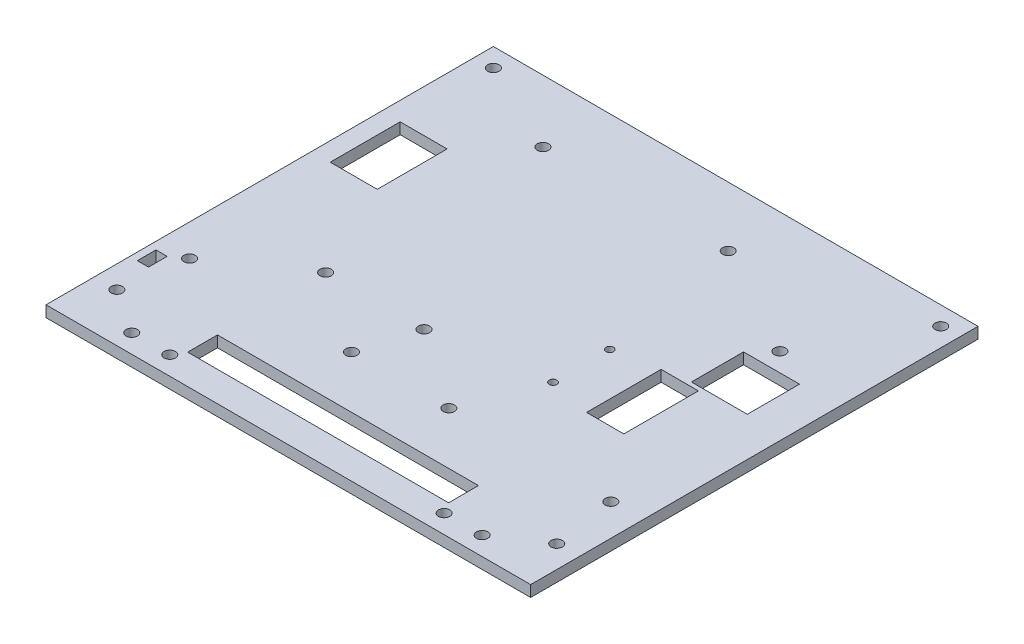
SolidWorks part; units mm, degrees
ref_plane "Front Plane" through (0, 0, 0) normal (0, 0, 1) x (1, 0, 0)
ref_plane "Top Plane" through (0, 0, 0) normal (0, 1, 0) x (1, 0, 0)
ref_plane "Right Plane" through (0, 0, 0) normal (1, 0, 0) x (0, 0, -1)
sketch "Sketch1" plane through (0, 0, 0) normal (0, 1, 0) x (1, 0, 0)
  line L0 (65, 0) -> (65, -120) construction
  line L1 (0, 0) -> (130, 0)
  line L2 (0, 0) -> (0, -92.5)
  line L3 (0, -120) -> (130, -120)
  line L4 (130, 0) -> (130, -92.5)
  line L5 (30, -104) -> (100, -104)
  line L6 (30, -104) -> (30, -112)
  line L7 (30, -112) -> (100, -112)
  line L8 (100, -104) -> (100, -112)
  line L9 (2, -92.5) -> (5, -92.5)
  line L10 (97.5, -52.5) -> (107.5, -52.5)
  line L11 (97.5, -52.5) -> (97.5, -72.5)
  line L12 (97.5, -72.5) -> (107.5, -72.5)
  line L13 (107.5, -52.5) -> (107.5, -72.5)
  line L14 (104.5, -51.38) -> (119.5, -51.38)
  line L15 (104.5, -51.38) -> (104.5, -37.38)
  line L16 (104.5, -37.38) -> (119.5, -37.38)
  line L17 (119.5, -51.38) -> (119.5, -37.38)
  line L18 (104.5, -51.38) -> (119.5, -37.38) construction
  line L19 (104.5, -37.38) -> (119.5, -51.38) construction
  line L20 (5, -92.5) -> (5, -97.5)
  line L21 (5, -97.5) -> (2, -97.5)
  line L25 (0, -97.5) -> (0, -120)
  line L26 (130, -97.5) -> (130, -120)
  line L27 (130, -97.5) -> (130, -92.5)
  line L28 (2, -92.5) -> (2, -97.5)
  line L29 (5, -30) -> (17.6, -30)
  line L30 (5, -30) -> (5, -48.75)
  line L31 (5, -48.75) -> (17.6, -48.75)
  line L32 (17.6, -30) -> (17.6, -48.75)
  line L33 (5, -30) -> (17.6, -48.75) construction
  line L34 (5, -48.75) -> (17.6, -30) construction
  line L35 (0, -97.5) -> (0, -92.5)
  circle A0 centre (28.2, -115) radius 1.525
  circle A1 centre (101.8, -115) radius 1.525
  circle A2 centre (121.5, -90) radius 1.525
  circle A3 centre (8.5, -90) radius 1.525
  circle A4 centre (78.06, -90) radius 1.525
  circle A5 centre (51.94, -90) radius 1.525
  circle A6 centre (124, -107) radius 1.525
  circle A7 centre (6, -107) radius 1.525
  circle A8 centre (30, -75) radius 1.525
  circle A9 centre (30, -16.71) radius 1.525
  circle A10 centre (56.4, -75) radius 1.525
  circle A11 centre (86, -70) radius 1.025
  circle A12 centre (86, -54.77) radius 1.025
  circle A13 centre (79, -16) radius 1.525
  circle A14 centre (109.24, -32.38) radius 1.525
  circle A15 centre (18, -115) radius 1.525
  circle A16 centre (112, -115) radius 1.525
  circle A17 centre (5, -5) radius 1.525
  circle A18 centre (125, -5) radius 1.525
  point P37 (102.5, -72.5)
  point P54 (112, -44.38)
  point P63 (11.3, -39.375)
  point P72 (0, 0)
  dimension "D4" = 3.05
  dimension "D6" = 11
  dimension "D9" = 28.2
  dimension "D11" = 3.05
  dimension "D12" = 8.5
  dimension "D13" = 30
  dimension "D18" = 45
  dimension "D22" = 2.05
  dimension "D1" = 130
  dimension "D2" = 120
  dimension "D3" = 70
  dimension "D5" = 5
  dimension "D7" = 8
  dimension "D8" = 30
  dimension "D10" = 28.2
  dimension "D14" = 51.94
  dimension "D15" = 6
  dimension "D16" = 13
  dimension "D17" = 30
  dimension "D19" = 58.29
  dimension "D20" = 56.4
  dimension "D21" = 44
  dimension "D23" = 15.23
  dimension "D24" = 50
  dimension "D25" = 20
  dimension "D26" = 10
  dimension "D27" = 22.5
  dimension "D28" = 47.5
  dimension "D29" = 51
  dimension "D30" = 16
  dimension "D31" = 20.76
  dimension "D32" = 32.38
  dimension "D33" = 18
  dimension "D34" = 5
  dimension "D35" = 5
  dimension "D36" = 15
  dimension "D37" = 14
  dimension "D38" = 18
  dimension "D39" = 5
  dimension "D40" = 22.5
  dimension "D41" = 5
  dimension "D42" = 5
  dimension "D43" = 12.6
  dimension "D44" = 18.75
  dimension "D45" = 5
  dimension "D46" = 30
  dimension "D47" = 2
extrude "Boss-Extrude1" add sketch "Sketch1" along normal blind 3 contours L0 L1 L2 L3 L7 L6 L5 A0 A3 | L1 L0 L5 L8 L7 L3 L4 A2 A1
